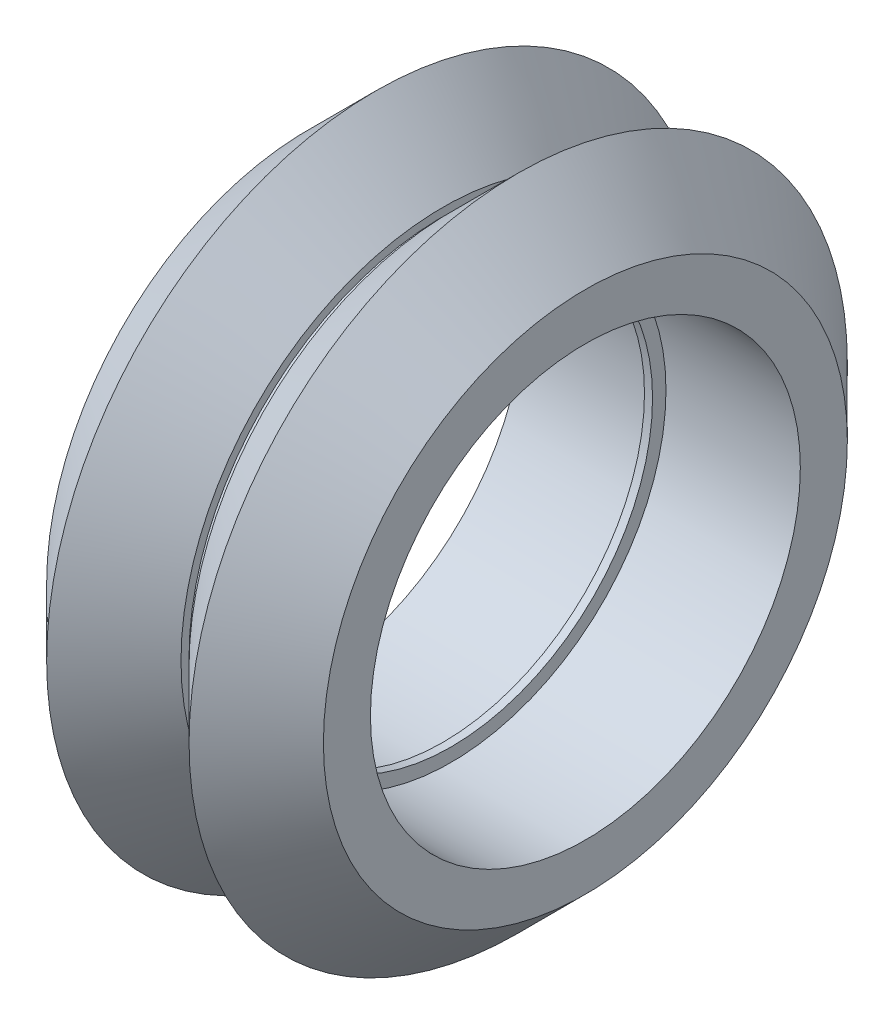
SolidWorks part; units mm, degrees
ref_plane "Plano frontal" through (0, 0, 0) normal (0, 0, 1) x (1, 0, 0)
ref_plane "Plano superior" through (0, 0, 0) normal (0, 1, 0) x (1, 0, 0)
ref_plane "Plano direito" through (0, 0, 0) normal (1, 0, 0) x (0, 0, -1)
sketch "Esboço1" plane through (0, 0, 0) normal (0, 0, 1) x (1, 0, 0)
  line L0 (-5.7739, 0) -> (6.125, 0) construction
  line L1 (-5.15, 9.75) -> (5.15, 9.75) construction
  line L3 (-5.15, 2.5) -> (-5.15, 9.75)
  line L5 (5.15, 2.5) -> (5.15, 9.75)
  line L6 (-5.15, 0) -> (5.15, 12.25) construction
  line L7 (-5.15, 12.25) -> (5.15, 0) construction
  line L8 (0, 12.25) -> (0, 9.75) construction
  line L9 (-5.15, 9.75) -> (-2.65, 12.25)
  line L10 (-2.65, 12.25) -> (-0.15, 9.75)
  line L11 (5.15, 9.75) -> (2.65, 12.25)
  line L12 (2.65, 12.25) -> (0.15, 9.75)
  line L13 (-0.15, 9.75) -> (-0.15, 9.45)
  line L14 (-0.15, 9.45) -> (0.15, 9.45)
  line L15 (0.15, 9.45) -> (0.15, 9.75)
  line L16 (-5.15, 2.5) -> (5.15, 2.5)
  point P3 (0, 6.125)
  dimension "D2" = 10.3
  dimension "D3" = 9.75
  dimension "D4" = 45
  dimension "D5" = 90
revolve "Revolução1" add sketch "Esboço1" angle 360 about L0
sketch "Esboço2" plane through (5.15, 0, 0) normal (1, 0, 0) x (0, 0, -1)
  circle A0 centre (0, 0) radius 8
  dimension "D1" = 16
extrude "Corte-extrusão1" cut sketch "Esboço2" against normal blind 5
sketch "Esboço3" plane through (-5.15, 0, 0) normal (-1, 0, 0) x (0, 0, 1)
  circle A0 centre (0, 0) radius 8
  dimension "D1" = 16
extrude "Corte-extrusão2" cut sketch "Esboço3" against normal blind 5
sketch "Esboço4" plane through (-0.15, 0, 0) normal (-1, 0, 0) x (0, 0, 1)
  circle A0 centre (0, 0) radius 7.5
  dimension "D1" = 15
extrude "Corte-extrusão3" cut sketch "Esboço4" against normal up to surface (0.3 mm away) up to face at (0.15, 0, -8)
